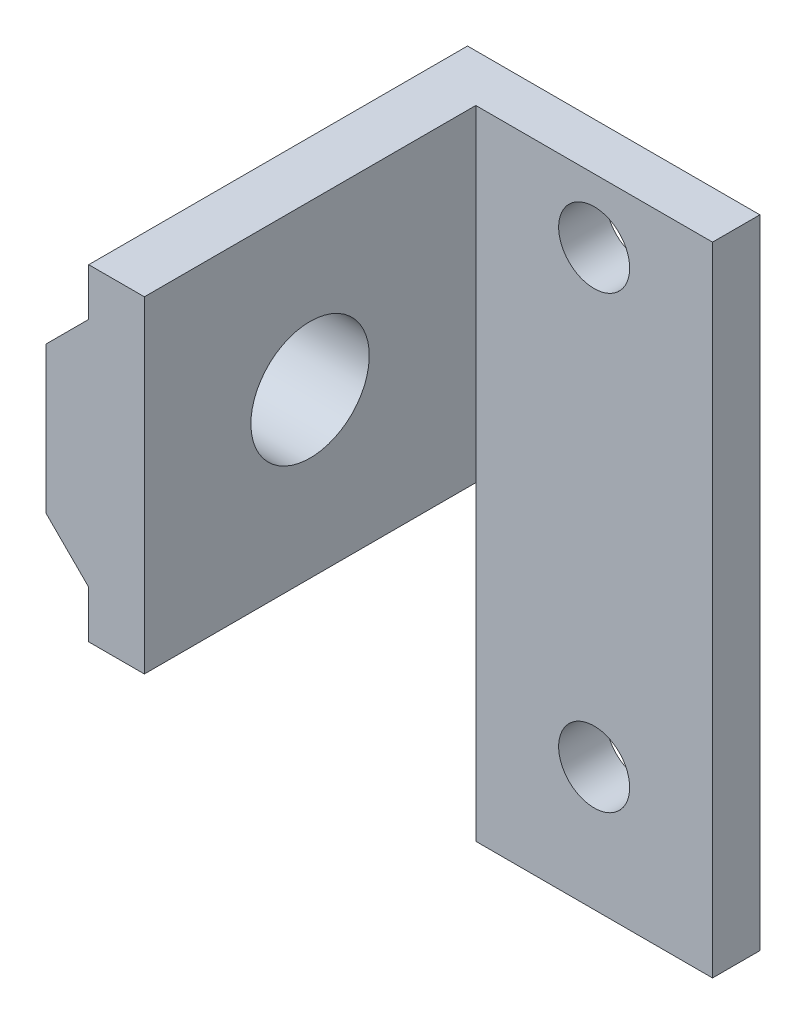
SolidWorks part; units mm, degrees
ref_plane "Front Plane" through (0, 0, 0) normal (0, 0, 1) x (1, 0, 0)
ref_plane "Top Plane" through (0, 0, 0) normal (0, 1, 0) x (1, 0, 0)
ref_plane "Right Plane" through (0, 0, 0) normal (1, 0, 0) x (0, 0, -1)
sketch "Sketch1" plane through (0, 0, 0) normal (0, 0, 1) x (1, 0, 0)
  line L0 (5, 24.22) -> (5, 5.22) construction
  line L1 (0, 0) -> (10, 0)
  line L2 (0, 0) -> (0, 26.92)
  line L3 (0, 26.92) -> (10, 26.92)
  line L4 (10, 0) -> (10, 26.92)
  circle A0 centre (5, 24.22) radius 1.5
  circle A1 centre (5, 5.22) radius 1.5
  dimension "D5" = 3
  dimension "D1" = 10
  dimension "D2" = 26.92
  dimension "D3" = 2.7
  dimension "D4" = 19
  dimension "D6" = 5
extrude "Boss-Extrude1" add sketch "Sketch1" along normal blind 2
sketch "Sketch2" plane through (0, 0, 0) normal (0, 0, -1) x (-1, 0, 0)
  line L1 (0, 26.92) -> (0, 0) construction
  line L2 (2.35, 24.92) -> (4.15, 23.12)
  line L3 (0, 24.92) -> (2.35, 24.92) construction
  line L7 (4.15, 23.12) -> (4.15, 16.92)
  line L8 (4.15, 16.92) -> (2.35, 15.12)
  line L9 (2.35, 15.12) -> (0, 15.12) construction
  line L10 (0, 15.12) -> (0, 24.92)
  line L11 (-10, 26.92) -> (0, 26.92) construction
  line L12 (2.35, 24.92) -> (0, 24.92) construction
  line L13 (2.35, 24.92) -> (2.35, 26.92)
  line L14 (2.35, 26.92) -> (0, 26.92)
  line L15 (0, 24.92) -> (0, 26.92)
  line L16 (0, 15.12) -> (2.35, 15.12) construction
  line L17 (0, 15.12) -> (0, 13.12)
  line L18 (0, 13.12) -> (2.35, 13.12)
  line L19 (2.35, 15.12) -> (2.35, 13.12)
  dimension "D1" = 2.35
  dimension "D2" = 4.15
  dimension "D4" = 45
  dimension "D5" = 9.8
  dimension "D6" = 2.5456
  dimension "D7" = 2
  dimension "D8" = 2
extrude "Boss-Extrude2" add sketch "Sketch2" against normal blind 16
sketch "Sketch5" plane through (0, 0, 0) normal (1, 0, 0) x (0, 0, -1)
  line L0 (-9, 26.92) -> (-9, 13.12) construction
  line L1 (-16, 26.92) -> (-2, 26.92) construction
  line L2 (-16, 13.12) -> (-2, 13.12) construction
  circle A0 centre (-9, 20.02) radius 2.5
  dimension "D1" = 5
extrude "Cut-Extrude1" cut sketch "Sketch5" against normal blind 16
